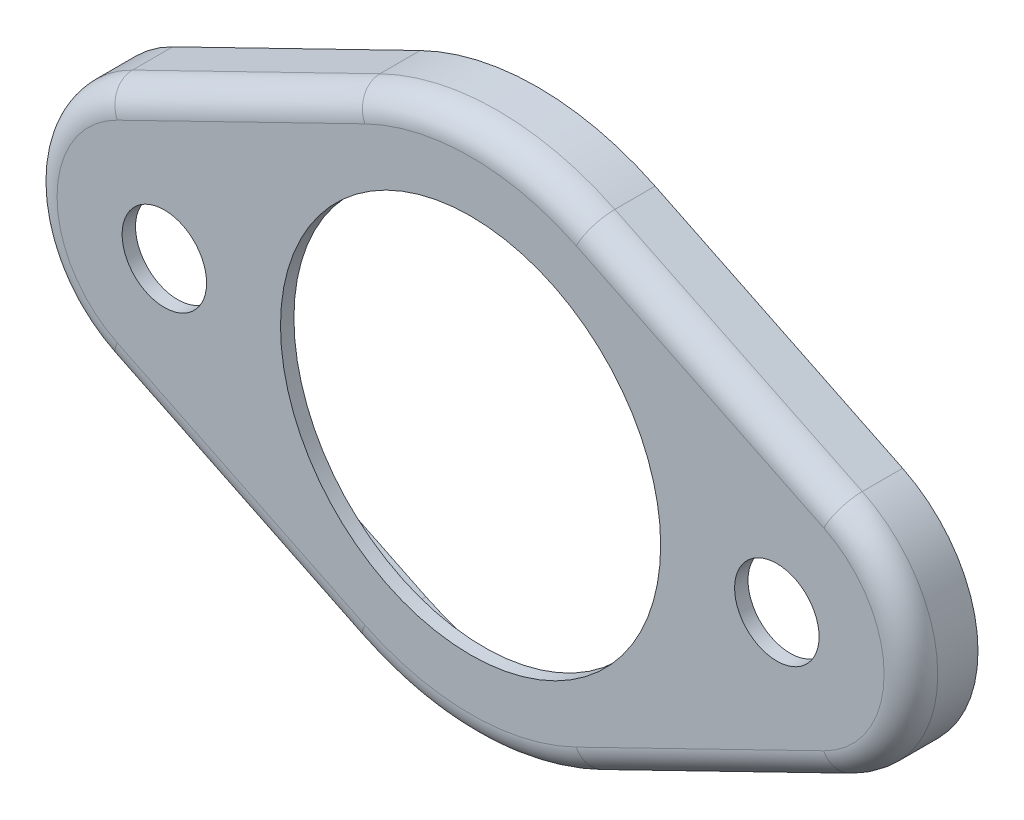
SolidWorks part; units mm, degrees
material "AISI 321 Annealed Stainless Steel (SS)"
ref_plane "Front Plane" through (0, 0, 0) normal (0, 0, 1) x (1, 0, 0)
ref_plane "Top Plane" through (0, 0, 0) normal (0, 1, 0) x (1, 0, 0)
ref_plane "Right Plane" through (0, 0, 0) normal (1, 0, 0) x (0, 0, -1)
sketch "Sketch1" plane through (0, 0, 0) normal (0, 0, 1) x (1, 0, 0)
  line L0 (-29, 0) -> (29, 0) construction
  line L1 (-34.5617, 11.4174) -> (-11.1234, 22.8348)
  line L2 (11.1234, 22.8348) -> (34.5617, 11.4174)
  line L3 (34.5617, -11.4174) -> (11.1234, -22.8348)
  line L4 (-11.1234, -22.8348) -> (-34.5617, -11.4174)
  circle A0 centre (-29, 0) radius 4
  circle A1 centre (29, 0) radius 4
  circle A2 centre (0, 0) radius 18
  arc A3 (-11.1234, 22.8348) -> (11.1234, 22.8348) centre (0, 0) cw
  arc A4 (-11.1234, -22.8348) -> (11.1234, -22.8348) centre (0, 0) ccw
  arc A5 (34.5617, 11.4174) -> (34.5617, -11.4174) centre (29, 0) cw
  arc A6 (-34.5617, 11.4174) -> (-34.5617, -11.4174) centre (-29, 0) ccw
  dimension "D1" = 8
  dimension "D2" = 8
  dimension "D5" = 36
  dimension "D6" = 12.7
  dimension "D7" = 12.7
  dimension "D8" = 25.4
  dimension "D9" = 25.4
  dimension "D3" = 58
  dimension "D4" = 29
extrude "Boss-Extrude1" add sketch "Sketch1" along normal blind 6.35
sketch "Sketch2" plane through (0, 0, 0) normal (0, 0, -1) x (-1, 0, 0)
  line L24 (34.0056, 10.2757) -> (10.5673, 21.6931)
  line L25 (10.5673, -21.6931) -> (34.0056, -10.2757)
  line L26 (-34.0056, -10.2757) -> (-10.5673, -21.6931)
  line L27 (-10.5673, 21.6931) -> (-34.0056, 10.2757)
  line L28 (34.0056, 10.2757) -> (10.5673, 21.6931)
  line L29 (10.5673, -21.6931) -> (34.0056, -10.2757)
  line L30 (-34.0056, -10.2757) -> (-10.5673, -21.6931)
  line L31 (-10.5673, 21.6931) -> (-34.0056, 10.2757)
  arc A21 (10.5673, 21.6931) -> (-10.5673, 21.6931) centre (0, 0) ccw
  arc A22 (34.0056, -10.2757) -> (34.0056, 10.2757) centre (29, 0) ccw
  arc A23 (-10.5673, -21.6931) -> (10.5673, -21.6931) centre (0, 0) ccw
  arc A24 (-34.0056, 10.2757) -> (-34.0056, -10.2757) centre (-29, 0) ccw
  arc A25 (10.5673, 21.6931) -> (-10.5673, 21.6931) centre (0, 0) ccw
  arc A26 (34.0056, -10.2757) -> (34.0056, 10.2757) centre (29, 0) ccw
  arc A27 (-10.5673, -21.6931) -> (10.5673, -21.6931) centre (0, 0) ccw
  arc A28 (-34.0056, 10.2757) -> (-34.0056, -10.2757) centre (-29, 0) ccw
  dimension "D1" = 1.27
extrude "Cut-Extrude1" cut sketch "Sketch2" against normal offset from surface (5.08 mm away) 1.27 up to face at (33, 0, 6.35)
fillet "Fillet1" radius 2.54 16 edges at (22.2864, -15.9844, 5.08) (0, -24.13, 5.08) (-22.2864, -15.9844, 5.08) (-40.43, 0, 5.08) (-22.2864, 15.9844, 5.08) (0, 24.13, 5.08) (22.2864, 15.9844, 5.08) (40.43, 0, 5.08) (22.8426, 17.1261, 6.35) (41.7, 0, 6.35) (22.8426, -17.1261, 6.35) (0, -25.4, 6.35) (-22.8426, -17.1261, 6.35) (-41.7, 0, 6.35) (-22.8426, 17.1261, 6.35) (0, 25.4, 6.35)
